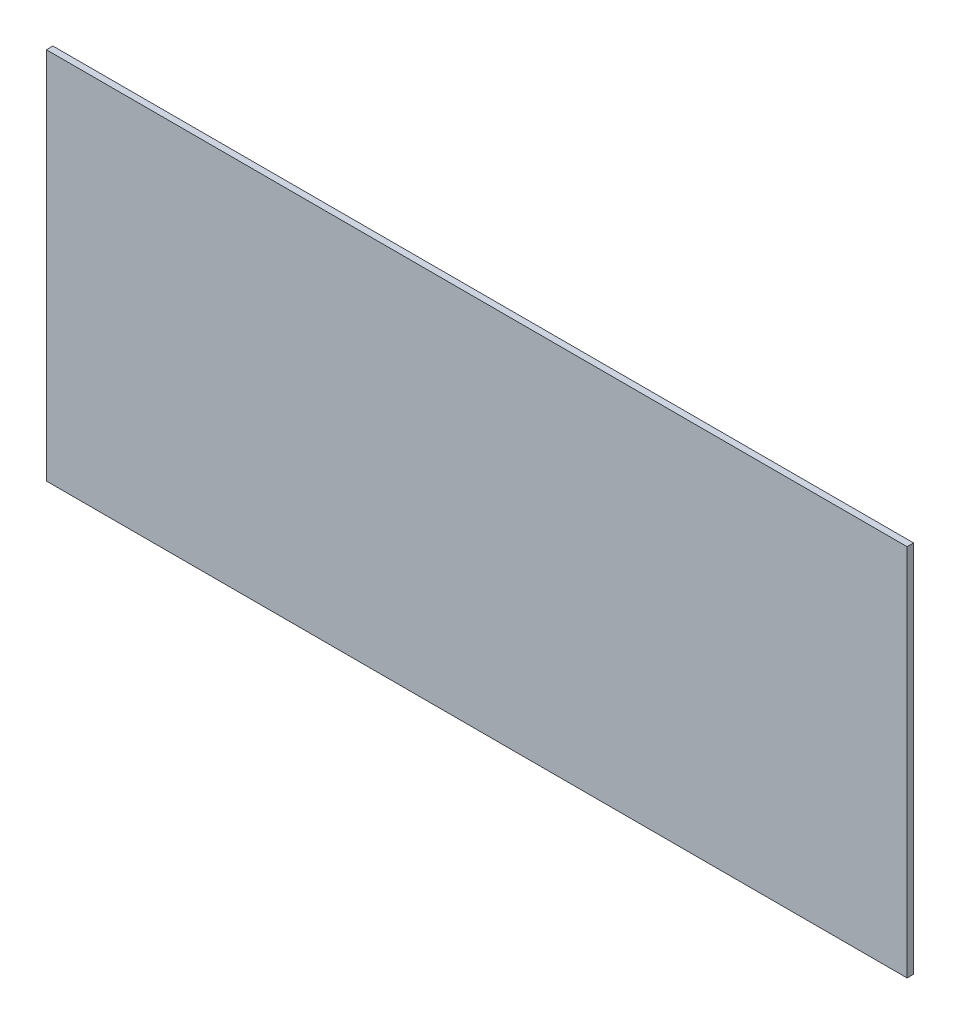
SolidWorks part; units mm, degrees
material "Fundición gris"
ref_plane "Alzado" through (0, 0, 0) normal (0, 0, 1) x (1, 0, 0)
ref_plane "Planta" through (0, 0, 0) normal (0, 1, 0) x (1, 0, 0)
ref_plane "Vista lateral" through (0, 0, 0) normal (1, 0, 0) x (0, 0, -1)
sketch "Croquis1" plane through (0, 0, 0) normal (0, 0, 1) x (1, 0, 0)
  line L1 (265, -115) -> (-265, -115)
  line L2 (265, -115) -> (265, 115)
  line L3 (265, 115) -> (-265, 115)
  line L4 (-265, -115) -> (-265, 115)
  line L5 (265, -115) -> (-265, 115) construction
  line L6 (265, 115) -> (-265, -115) construction
  point P0 (0, 0)
  dimension "D1" = 530
  dimension "D2" = 230
extrude "Saliente-Extruir1" add sketch "Croquis1" along normal blind 4
